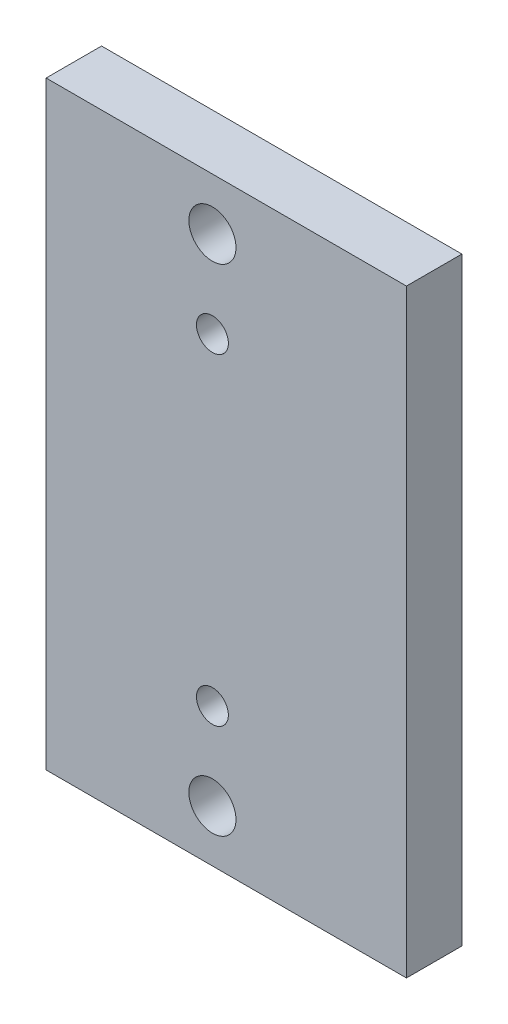
SolidWorks part; units mm, degrees
material "ABS"
ref_plane "Front Plane" through (0, 0, 0) normal (0, 0, 1) x (1, 0, 0)
ref_plane "Top Plane" through (0, 0, 0) normal (0, 1, 0) x (1, 0, 0)
ref_plane "Right Plane" through (0, 0, 0) normal (1, 0, 0) x (0, 0, -1)
sketch "Sketch1" plane through (0, 0, 0) normal (0, 0, 1) x (1, 0, 0)
  line L0 (-4, -16.62) -> (22, -16.62)
  line L1 (22, -16.62) -> (22, 26.62)
  line L2 (22, 26.62) -> (-4, 26.62)
  line L3 (-4, 26.62) -> (-4, -16.62)
  circle A0 centre (8, -12.87) radius 1.7
  circle A1 centre (8, 22.87) radius 1.7
  circle A2 centre (8, -6.62) radius 1.15
  circle A3 centre (8, 16.62) radius 1.15
  dimension "D3" = 3.4
  dimension "D6" = 2.3
  dimension "D1" = 26
  dimension "D2" = 43.24
  dimension "D4" = 12
  dimension "D5" = 3.75
  dimension "D7" = 10
extrude "Boss-Extrude1" add sketch "Sketch1" along normal blind 4
